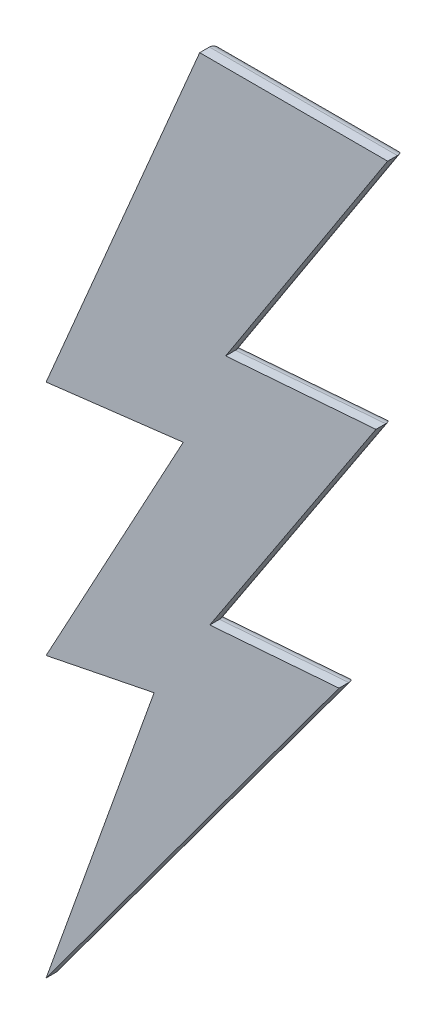
SolidWorks part; units mm, degrees
ref_plane "Płaszczyzna przednia" through (0, 0, 0) normal (0, 0, 1) x (1, 0, 0)
ref_plane "Płaszczyzna górna" through (0, 0, 0) normal (0, 1, 0) x (1, 0, 0)
ref_plane "Płaszczyzna prawa" through (0, 0, 0) normal (1, 0, 0) x (0, 0, -1)
sketch "Szkic1" plane through (0, 0, 0) normal (0, 0, 1) x (1, 0, 0)
  line L0 (35, 90) -> (15.7385, 90)
  line L1 (0, 90) -> (35, 90) construction
  line L2 (0, 90) -> (0, 0) construction
  line L3 (0, 0) -> (35, 0) construction
  line L4 (35, 90) -> (35, 0) construction
  line L7 (15.7385, 90) -> (0, 52.8929)
  line L8 (0, 52.8929) -> (14.0546, 54.5768)
  line L9 (14.0546, 54.5768) -> (0, 28.6256)
  line L10 (0, 28.6256) -> (11.0647, 30.849)
  line L11 (11.0647, 30.849) -> (0, 0)
  line L12 (0, 0) -> (30.0194, 40.7382)
  line L13 (30.0194, 40.7382) -> (16.7721, 39.7192)
  line L14 (16.7721, 39.7192) -> (33.8031, 65.5988)
  line L15 (33.8031, 65.5988) -> (18.3994, 64.4139)
  line L16 (18.3994, 64.4139) -> (35, 90)
  point P0 (17.5, 45)
  point P5 (17.6357, 92.082)
  point P6 (0, 0)
  point P16 (15.7385, 90)
  point P17 (12.3472, 58.2501)
  point P18 (12.0645, 55.3422)
  point P19 (0, 52.4336)
  point P20 (12.6768, 53.8114)
  point P21 (0, 52.8929)
  point P22 (0, 29.012)
  point P23 (13.5953, 52.8929)
  point P24 (14.0546, 54.5768)
  point P25 (0, 30.849)
  point P26 (16.7721, 39.7192)
  point P27 (11.0647, 30.849)
  point P28 (0, 28.6256)
  dimension "D1" = 90
  dimension "D2" = 35
extrude "Dodanie-wyciągnięcie1" add sketch "Szkic1" along normal blind 2
fillet "Zaokrąglenie1" radius 1 11 edges at (23.3957, 40.2287, 0) (25.2876, 52.659, 0) (26.1013, 65.0063, 0) (26.6997, 77.2069, 0) (25.3692, 90, 0) (7.8692, 71.4464, 0) (7.0273, 53.7348, 0) (7.0273, 41.6012, 0) (5.5324, 29.7373, 0) (5.5324, 15.4245, 0) (15.0097, 20.3691, 0)
other "Narzędzie formowania1"
sketch "Szkic orientacji" plane through (0, 0, 2) normal (0, 0, 1) x (1, 0, 0)
  line L0 (0, 0) -> (30.0194, 40.7382) construction
  line L1 (30.0194, 40.7382) -> (16.7721, 39.7192) construction
  line L2 (16.7721, 39.7192) -> (33.8031, 65.5988) construction
  line L3 (33.8031, 65.5988) -> (18.3994, 64.4139) construction
  line L4 (18.3994, 64.4139) -> (35, 90) construction
  line L5 (35, 90) -> (15.7385, 90) construction
  line L6 (15.7385, 90) -> (0, 52.8929) construction
  line L7 (0, 52.8929) -> (14.0546, 54.5768) construction
  line L8 (14.0546, 54.5768) -> (0, 28.6256) construction
  line L9 (0, 28.6256) -> (11.0647, 30.849) construction
  line L10 (11.0647, 30.849) -> (0, 0) construction
  line L11 (0, 0) -> (30.0194, 40.7382)
  line L12 (30.0194, 40.7382) -> (16.7721, 39.7192)
  line L13 (16.7721, 39.7192) -> (33.8031, 65.5988)
  line L14 (33.8031, 65.5988) -> (18.3994, 64.4139)
  line L15 (18.3994, 64.4139) -> (35, 90)
  line L16 (35, 90) -> (15.7385, 90)
  line L17 (15.7385, 90) -> (0, 52.8929)
  line L18 (0, 52.8929) -> (14.0546, 54.5768)
  line L19 (14.0546, 54.5768) -> (0, 28.6256)
  line L20 (0, 28.6256) -> (11.0647, 30.849)
  line L21 (11.0647, 30.849) -> (0, 0)
  point P2 (17.5, 45)
